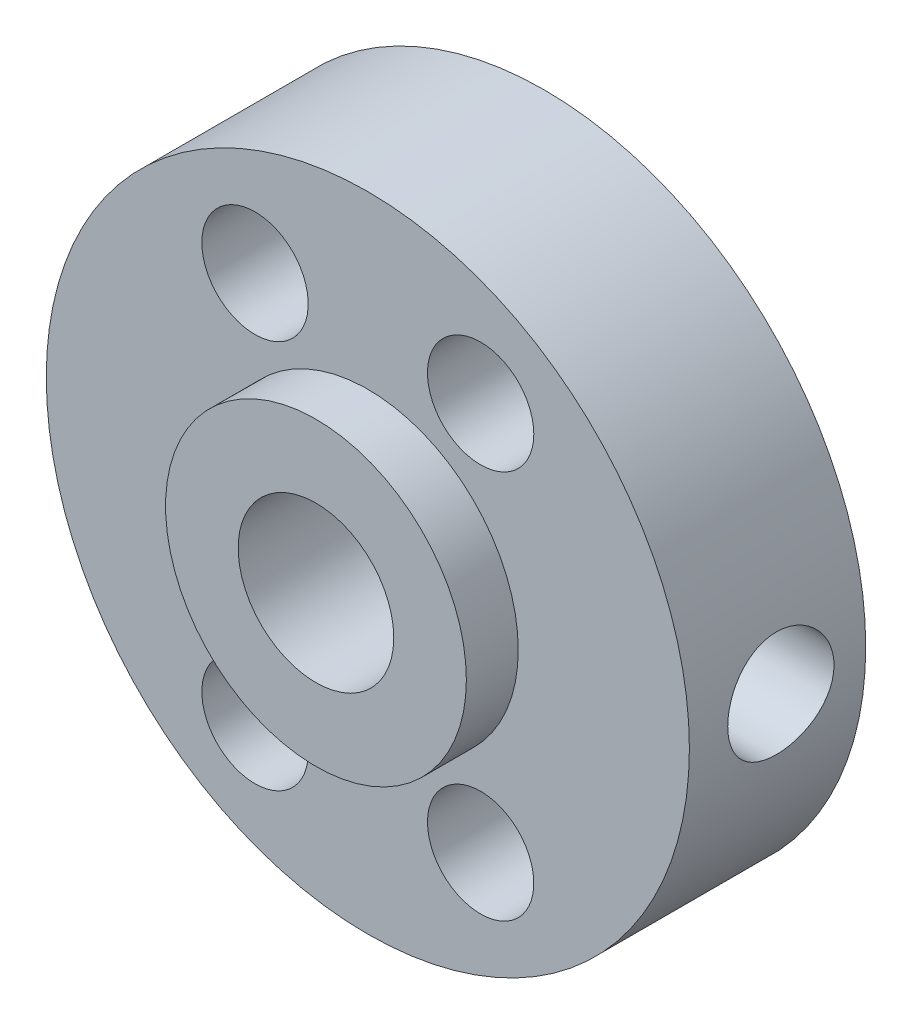
SolidWorks part; units mm, degrees
ref_plane "Front Plane" through (0, 0, 0) normal (0, 0, 1) x (1, 0, 0)
ref_plane "Top Plane" through (0, 0, 0) normal (0, 1, 0) x (1, 0, 0)
ref_plane "Right Plane" through (0, 0, 0) normal (1, 0, 0) x (0, 0, -1)
sketch "Sketch1" plane through (0, 0, 0) normal (0, 0, 1) x (1, 0, 0)
  circle A0 centre (0, 0) radius 12.4
  dimension "D1" = 24.8
extrude "Boss-Extrude1" add sketch "Sketch1" along normal blind 6.8
sketch "Sketch2" plane through (0, 0, 6.8) normal (0, 0, 1) x (1, 0, 0)
  circle A0 centre (0, 0) radius 5.8
  dimension "D1" = 11.6
extrude "Boss-Extrude2" add sketch "Sketch2" along normal blind 2
sketch "Sketch3" plane through (0, 0, 8.8) normal (0, 0, 1) x (1, 0, 0)
  circle A0 centre (0, 0) radius 3
extrude "Cut-Extrude1" cut sketch "Sketch3" against normal through all
sketch "Sketch4" plane through (0, 0, 6.8) normal (0, 0, 1) x (1, 0, 0)
  line L0 (0, -1.3192) -> (0, 0.9734) construction
  line L1 (0, 0) -> (1.6706, 0) construction
  circle A0 centre (4.35, 7.5) radius 2.05
  circle A1 centre (-4.35, 7.5) radius 2.05
  circle A2 centre (4.35, -7.5) radius 2.05
  circle A3 centre (-4.35, -7.5) radius 2.05
  point P11 (4.7526, 7.5)
  dimension "D1" = 4.1
  dimension "D2" = 4.35
  dimension "D3" = 7.5
extrude "Cut-Extrude2" cut sketch "Sketch4" against normal through all
ref_plane "Plane1" through (12.4, 0, 0) normal (1, 0, 0) x (0, 0, -1)
sketch "Sketch5" plane through (12.4, 0, 0) normal (1, 0, 0) x (0, 0, -1)
  circle A0 centre (-3.2718, 0) radius 2.05
  dimension "D1" = 4.1
extrude "Cut-Extrude3" cut sketch "Sketch5" against normal blind 6
